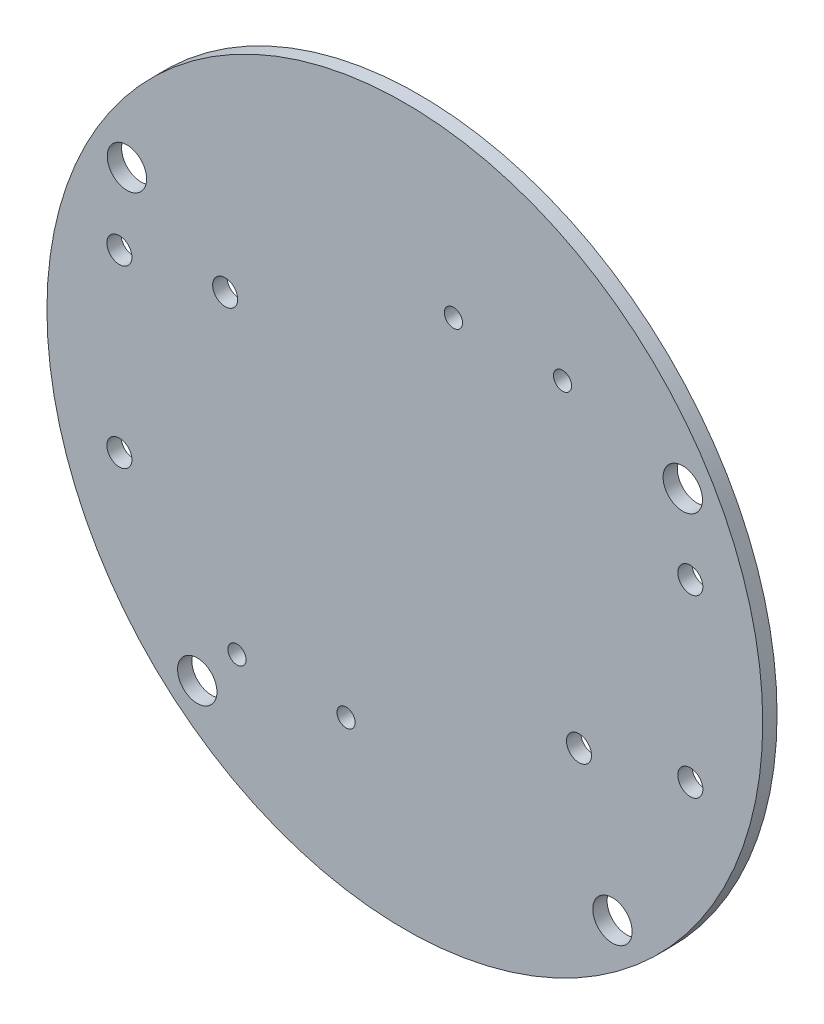
SolidWorks part; units mm, degrees
ref_plane "Plano frontal" through (0, 0, 0) normal (0, 0, 1) x (1, 0, 0)
ref_plane "Plano superior" through (0, 0, 0) normal (0, 1, 0) x (1, 0, 0)
ref_plane "Plano direito" through (0, 0, 0) normal (1, 0, 0) x (0, 0, -1)
sketch "Esboço1" plane through (0, 0, 0) normal (0, 0, 1) x (1, 0, 0)
  circle A0 centre (0, 0) radius 50
  dimension "D1" = 100
extrude "Ressalto-extrusão1" add sketch "Esboço1" along normal blind 2
sketch "Esboço2" plane through (0, 0, 2) normal (0, 0, 1) x (1, 0, 0)
  line L0 (0, 0) -> (0, 68.6386) construction
  line L1 (-61.9657, 0) -> (66.0984, 0) construction
  line L2 (-61.9657, -34.4093) -> (66.0984, -34.4093) construction
  line L3 (-65.4234, 22.88) -> (52.1255, 22.88) construction
  circle A4 centre (-29, -34.4093) radius 2.75
  circle A5 centre (29, -34.4093) radius 2.75
  circle A6 centre (-38.8242, 22.7526) radius 2.75
  circle A7 centre (38.8242, 22.7526) radius 2.75
  point P9 (2.9328, -3.8481)
  dimension "D1" = 58
  dimension "D4" = 45
  dimension "D2" = 45
  dimension "D8" = 5.5
  dimension "D9" = 5.5
  dimension "D10" = 5.5
  dimension "D11" = 5.5
  dimension "D3" = 45
  dimension "D5" = 45
  dimension "D6" = 58
  dimension "D7" = 58
extrude "Corte-extrusão1" cut sketch "Esboço2" against normal blind 2
sketch "Esboço3" plane through (0, 0, 2) normal (0, 0, 1) x (1, 0, 0)
  line L0 (71.0424, 0) -> (-71.0424, 0) construction
  line L1 (0, -53.8288) -> (0, 53.8288) construction
  circle A0 centre (-25.1, 14.54) radius 1.75
  circle A1 centre (24.33, -15.91) radius 1.75
  circle A2 centre (-39.88, -12.25) radius 1.75
  circle A3 centre (-39.88, 12.25) radius 1.75
  circle A4 centre (39.88, 12.25) radius 1.75
  circle A5 centre (39.88, -12.25) radius 1.75
  circle A6 centre (6.79, 27.4) radius 1.27
  circle A7 centre (22.03, 27.4) radius 1.27
  circle A8 centre (-8.21, -28.46) radius 1.27
  circle A9 centre (-23.45, -28.46) radius 1.27
  point P4 (0, 0)
  point P8 (0, 0)
  dimension "D1" = 3.5
  dimension "D6" = 12.25
  dimension "D14" = 27.4
  dimension "D2" = 25.1
  dimension "D3" = 14.54
  dimension "D4" = 24.33
  dimension "D5" = 15.91
  dimension "D7" = 12.25
  dimension "D8" = 39.88
  dimension "D9" = 39.88
  dimension "D10" = 12.25
  dimension "D11" = 12.25
  dimension "D12" = 39.88
  dimension "D13" = 39.88
  dimension "D15" = 27.4
  dimension "D16" = 6.79
  dimension "D17" = 22.03
  dimension "D18" = 28.46
  dimension "D19" = 28.46
  dimension "D20" = 8.21
  dimension "D21" = 23.45
extrude "Corte-extrusão2" cut sketch "Esboço3" against normal blind 10
